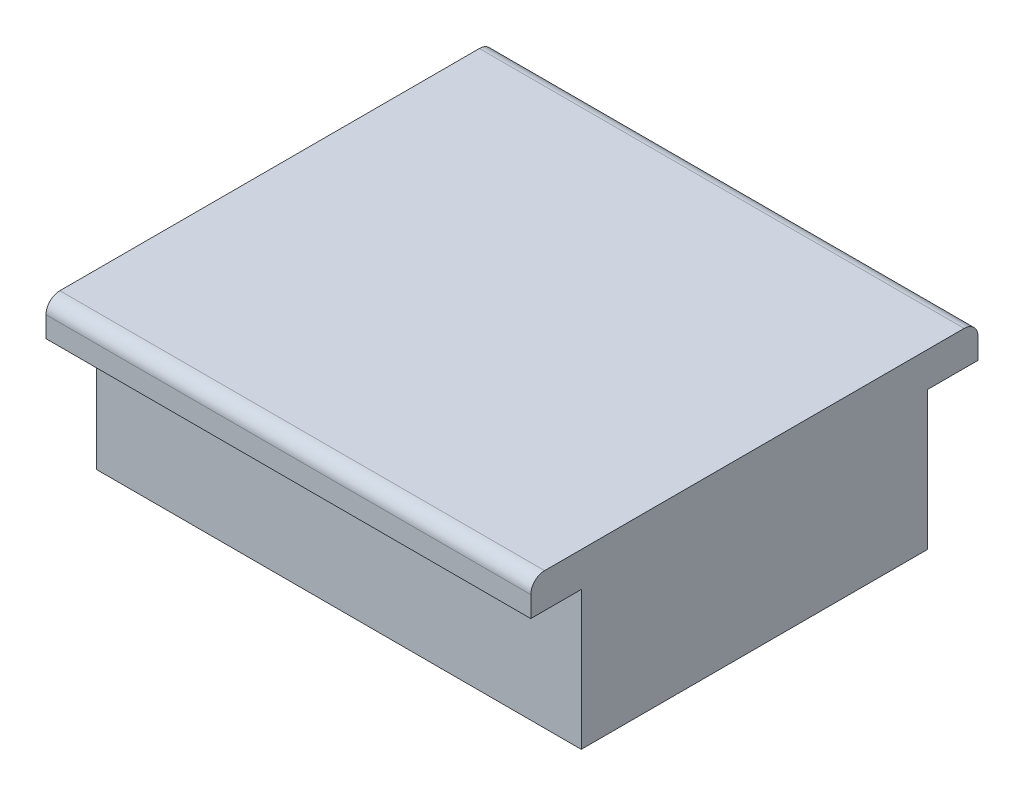
SolidWorks part; units mm, degrees
ref_plane "Front Plane" through (0, 0, 0) normal (0, 0, 1) x (1, 0, 0)
ref_plane "Top Plane" through (0, 0, 0) normal (0, 1, 0) x (1, 0, 0)
ref_plane "Right Plane" through (0, 0, 0) normal (1, 0, 0) x (0, 0, -1)
sketch "Sketch1" plane through (0, 0, 0) normal (1, 0, 0) x (0, 0, -1)
  line L0 (0, 0) -> (1270, 0)
  line L1 (1270, 0) -> (1270, 508)
  line L2 (1270, 508) -> (1455.0969, 508)
  line L3 (1455.0969, 508) -> (1455.0969, 584.2)
  line L4 (1404.2969, 635) -> (-134.2969, 635)
  line L5 (-185.0969, 584.2) -> (-185.0969, 508)
  line L6 (-185.0969, 508) -> (0, 508)
  line L7 (0, 508) -> (0, 0)
  arc A0 (1455.0969, 584.2) -> (1404.2969, 635) centre (1404.2969, 584.2) ccw
  arc A1 (-134.2969, 635) -> (-185.0969, 584.2) centre (-134.2969, 584.2) ccw
  point P13 (-185.0969, 635)
  dimension "D5" = 50.8
  dimension "D1" = 1270
  dimension "D2" = 508
  dimension "D3" = 127
  dimension "D4" = 508
extrude "Boss-Extrude1" add sketch "Sketch1" along normal blind 1778
sketch "Sketch2" plane through (0, 635, 0) normal (0, 1, 0) x (1, 0, 0)
  line L1 (1778, 1455.0969) -> (0, 1455.0969) construction
  line L2 (1778, -185.0969) -> (0, -185.0969) construction
  line L3 (0, 1404.2969) -> (0, -134.2969) construction
  circle A0 centre (889, 703.9031) radius 63.5
  dimension "D1" = 127
  dimension "D2" = 889
  dimension "D3" = 889
  dimension "D4" = 1640.1938
